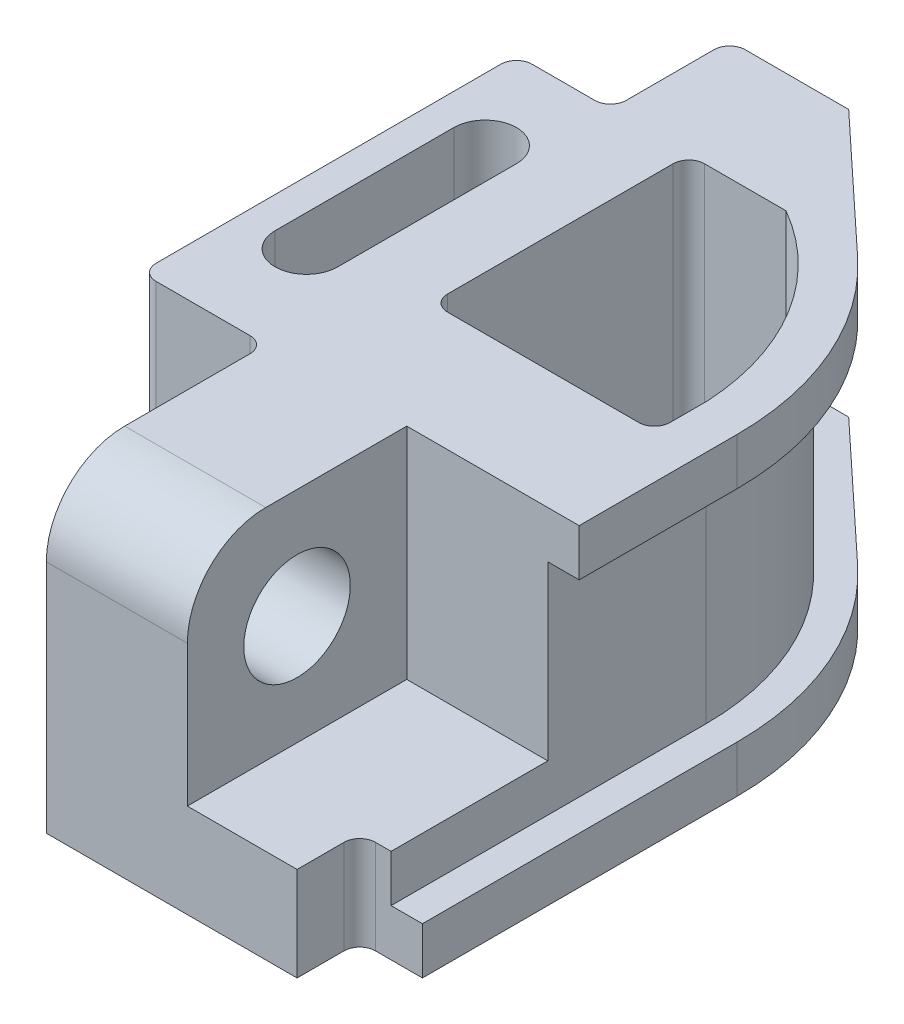
SolidWorks part; units mm, degrees
ref_plane "Front Plane" through (0, 0, 0) normal (0, 0, 1) x (1, 0, 0)
ref_plane "Top Plane" through (0, 0, 0) normal (0, 1, 0) x (1, 0, 0)
ref_plane "Right Plane" through (0, 0, 0) normal (1, 0, 0) x (0, 0, -1)
sketch "Sketch1" plane through (0, 0, 0) normal (0, 1, 0) x (1, 0, 0)
  line L0 (0, 5) -> (0, 115)
  line L1 (5, 120) -> (25, 120)
  line L2 (30, 125) -> (30, 153)
  line L3 (35, 158) -> (68, 158)
  line L4 (110.4258, 118.4373) -> (68, 158)
  line L5 (140, 50.4214) -> (140, -50)
  line L6 (140, -50) -> (125, -50)
  line L7 (120, -55) -> (120, -70)
  line L8 (120, -70) -> (40, -70)
  line L9 (40, -70) -> (40, -5)
  line L10 (35, 0) -> (5, 0)
  arc A0 (110.4258, 118.4373) -> (140, 50.4214) centre (47, 50.4214) cw
  arc A1 (125, -50) -> (120, -55) centre (125, -55) ccw
  arc A2 (40, -5) -> (35, 0) centre (35, -5) ccw
  arc A3 (0, 115) -> (5, 120) centre (5, 115) cw
  arc A4 (25, 120) -> (30, 125) centre (25, 125) ccw
  arc A5 (30, 153) -> (35, 158) centre (35, 153) cw
  arc A6 (5, 0) -> (0, 5) centre (5, 5) cw
  point P17 (120, -50)
  point P20 (40, 0)
  point P22 (0, 120)
  point P25 (30, 120)
  point P28 (30, 158)
  point P31 (0, 0)
  dimension "D8" = 30
  dimension "D3" = 38
  dimension "D6" = 93
  dimension "D12" = 5
  dimension "D13" = 5
  dimension "D14" = 5
  dimension "D15" = 5
  dimension "D16" = 5
  dimension "D17" = 5
  dimension "D1" = 120
  dimension "D2" = 35
  dimension "D4" = 38
  dimension "D5" = 70
  dimension "D7" = 20
  dimension "D9" = 140
  dimension "D10" = 20
  dimension "D11" = 137
extrude "Boss-Extrude1" add sketch "Sketch1" along normal blind 100
ref_plane "Plane1" through (0, 15, 0) normal (0, -1, 0) x (-1, 0, 0)
sketch "Sketch2" plane through (0, 15, 0) normal (0, -1, 0) x (-1, 0, 0)
  line L0 (-53.3372, 158) -> (-103.6059, 111.1237)
  line L1 (-68, 158) -> (-35, 158) construction
  line L2 (-130, 50.4214) -> (-130, -50)
  line L3 (-110.4258, 118.4373) -> (-68, 158) construction
  line L4 (-140, -50) -> (-140, 50.4214) construction
  line L5 (-125, -50) -> (-140, -50) construction
  line L6 (-53.3372, 158) -> (-68, 158)
  line L7 (-68, 158) -> (-110.4258, 118.4373)
  line L8 (-140, 50.4214) -> (-140, -50)
  line L9 (-140, -50) -> (-130, -50)
  arc A0 (-103.6059, 111.1237) -> (-130, 50.4214) centre (-47, 50.4214) ccw
  arc A1 (-110.4258, 118.4373) -> (-140, 50.4214) centre (-47, 50.4214) ccw construction
  arc A2 (-110.4258, 118.4373) -> (-140, 50.4214) centre (-47, 50.4214) ccw
  dimension "D1" = 10
extrude "Cut-Extrude1" cut sketch "Sketch2" against normal blind 70
sketch "Sketch3" plane through (0, 100, 0) normal (0, 1, 0) x (1, 0, 0)
  line L0 (140, 0) -> (85, 0)
  line L1 (140, -50) -> (140, 50.4214) construction
  line L2 (85, 0) -> (85, -70)
  line L3 (40, -70) -> (120, -70) construction
  line L4 (140, 0) -> (140, -70)
  line L5 (140, -70) -> (85, -70)
  dimension "D1" = 55
  dimension "D2" = 70
extrude "Cut-Extrude2" cut sketch "Sketch3" against normal blind 70
fillet "Fillet1" radius 25 1 edges at (62.5, 100, 70)
sketch "Sketch4" plane through (40, 0, 0) normal (-1, 0, 0) x (0, 0, 1)
  line L2 (5, 100) -> (45, 100) construction
  line L3 (70, 75) -> (70, 0) construction
  circle A0 centre (35, 65) radius 17
  dimension "D3" = 34
  dimension "D1" = 35
  dimension "D2" = 35
extrude "Cut-Extrude3" cut sketch "Sketch4" against normal up to next
sketch "Sketch5" plane through (0, 100, 0) normal (0, 1, 0) x (1, 0, 0)
  line L0 (20, 90) -> (20, 33) construction
  line L1 (30, 90) -> (30, 33)
  line L2 (10, 90) -> (10, 33)
  line L5 (0, 115) -> (0, 5) construction
  line L7 (5, 0) -> (35, 0) construction
  arc A0 (30, 90) -> (10, 90) centre (20, 90) ccw
  arc A1 (10, 33) -> (30, 33) centre (20, 33) ccw
  point P2 (20, 61.5)
  point P11 (20, 0)
  dimension "D3" = 10
  dimension "D1" = 33
  dimension "D2" = 57
  dimension "D4" = 30
extrude "Cut-Extrude4" cut sketch "Sketch5" against normal blind 25
sketch "Sketch6" plane through (0, 0, 0) normal (0, -1, 0) x (1, 0, 0)
  line L0 (20, -33) -> (20, -90) construction
  line L1 (30, -33) -> (30, -90)
  line L2 (10, -33) -> (10, -90)
  arc A0 (30, -33) -> (10, -33) centre (20, -33) ccw
  arc A1 (10, -90) -> (30, -90) centre (20, -90) ccw
  point P4 (20, -61.5)
  dimension "D1" = 10
extrude "Cut-Extrude5" cut sketch "Sketch6" against normal blind 25
sketch "Sketch7" plane through (0, 100, 0) normal (0, 1, 0) x (1, 0, 0)
  line L0 (55, 115) -> (55, 43)
  line L1 (60, 38) -> (121, 38)
  line L2 (86, 120) -> (60, 120)
  line L3 (126, 55) -> (126, 43)
  line L5 (25, 120) -> (5, 120) construction
  line L6 (30, 90) -> (30, 33) construction
  arc A0 (86, 120) -> (126, 55) centre (46.1184, 50.6498) cw
  arc A3 (60, 120) -> (55, 115) centre (60, 115) ccw
  arc A4 (60, 38) -> (55, 43) centre (60, 43) cw
  arc A5 (126, 43) -> (121, 38) centre (121, 43) cw
  point P12 (55, 120)
  point P15 (55, 38)
  point P18 (126, 38)
  dimension "D4" = 80
  dimension "D7" = 5
  dimension "D8" = 5
  dimension "D9" = 5
  dimension "D1" = 82
  dimension "D2" = 71
  dimension "D3" = 17
  dimension "D5" = 31
  dimension "D6" = 25
extrude "Cut-Extrude6" cut sketch "Sketch7" against normal blind 85
